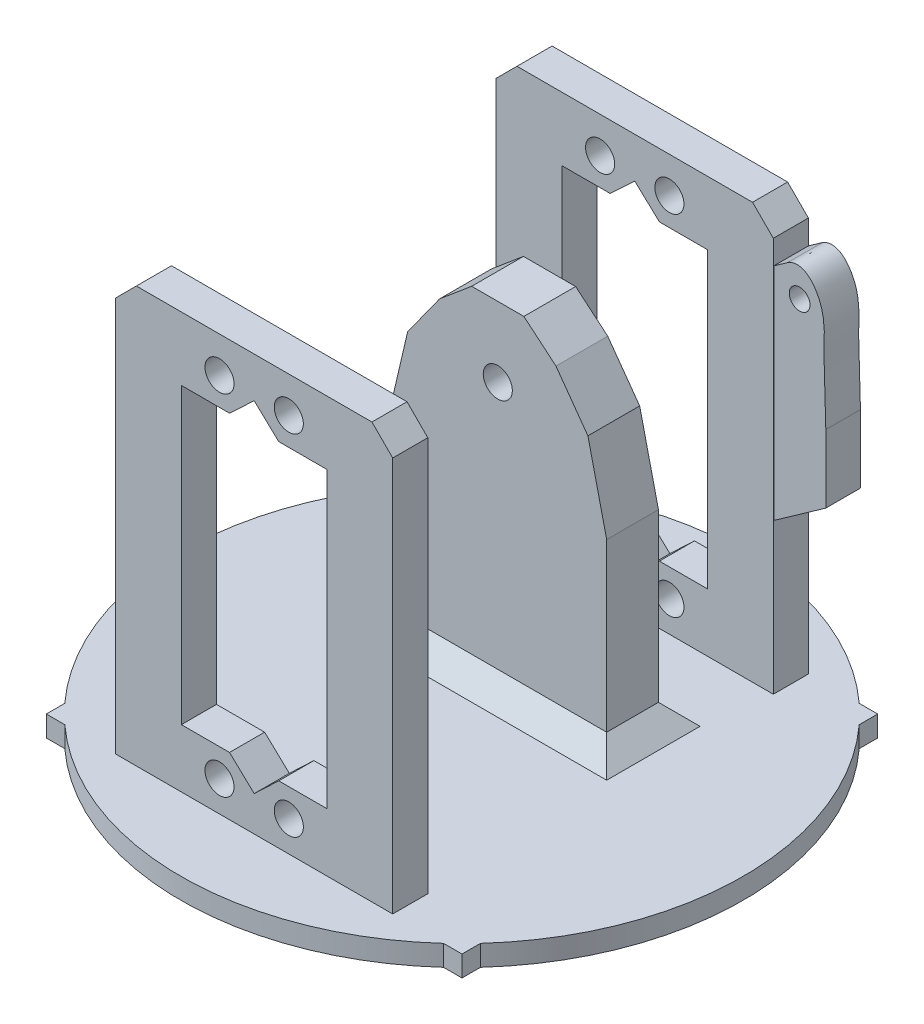
SolidWorks part; units mm, degrees
ref_plane "Plan de face" through (0, 0, 0) normal (0, 0, 1) x (1, 0, 0)
ref_plane "Plan de dessus" through (0, 0, 0) normal (0, 1, 0) x (1, 0, 0)
ref_plane "Plan de droite" through (0, 0, 0) normal (1, 0, 0) x (0, 0, -1)
sketch "Esquisse1" plane through (0, 0, 0) normal (0, 1, 0) x (1, 0, 0)
  line L1 (30, -30) -> (-30, -30)
  line L2 (30, -30) -> (30, 30)
  line L3 (30, 30) -> (-30, 30)
  line L4 (-30, -30) -> (-30, 30)
  line L5 (30, -30) -> (-30, 30) construction
  line L6 (30, 30) -> (-30, -30) construction
  point P0 (0, 0)
  dimension "D1" = 60
  dimension "D2" = 60
extrude "Boss.-Extru.1" add sketch "Esquisse1" along normal blind 3
sketch "Esquisse2" plane through (0, 3, 0) normal (0, 1, 0) x (1, 0, 0)
  line L0 (20, -30) -> (-20, -30)
  line L1 (-30, -30) -> (30, -30) construction
  line L2 (0, -1.65) -> (0, 1.65) construction
  line L3 (-1.65, 0) -> (1.65, 0) construction
  line L4 (20, 30) -> (-20, 30)
  line L5 (-20, -30) -> (-20, -24.9359)
  line L6 (-20, -24.9359) -> (20, -24.9359)
  line L7 (20, -24.9359) -> (20, -30)
  line L8 (-20, 30) -> (-20, 24.9359)
  line L9 (-20, 24.9359) -> (20, 24.9359)
  line L10 (20, 24.9359) -> (20, 30)
  point P7 (0, -30)
  point P11 (-20, -27.468)
  point P16 (-20, 27.468)
  dimension "D1" = 20
extrude "Boss.-Extru.2" add sketch "Esquisse2" along normal blind 60
sketch "Esquisse3" plane through (0, 0, 30) normal (0, 0, 1) x (1, 0, 0)
  line L0 (0, -37.675) -> (0, 37.675) construction
  line L5 (10.5, 53.8193) -> (-10.5, 53.8193)
  line L6 (10.5, 11.4193) -> (-10.5, 11.4193)
  line L7 (-10.5, 53.8193) -> (-10.5, 11.4193)
  line L8 (10.5, 53.8193) -> (10.5, 11.4193)
  circle A0 centre (-5, 57.8193) radius 2.1
  circle A1 centre (5, 57.8193) radius 2.1
  circle A2 centre (-5, 7.4193) radius 2.1
  circle A3 centre (5, 7.4193) radius 2.1
  point P13 (0, 53.8193)
  point P16 (0, 11.4193)
  dimension "D1" = 10
  dimension "D2" = 10
  dimension "D7" = 4.2
  dimension "D3" = 50.4
  dimension "D4" = 4
  dimension "D5" = 4
  dimension "D6" = 10.5
extrude "Enlèv. mat.-Extru.1" cut sketch "Esquisse3" against normal blind 61
sketch "Esquisse4" plane through (0, 3, 0) normal (0, 1, 0) x (1, 0, 0)
  line L0 (0, -37.675) -> (0, 37.675) construction
  line L1 (-15.7182, 5.1641) -> (15.7182, 5.1641)
  line L2 (-15.7182, 5.1641) -> (-15.7182, 12.6359)
  line L3 (-15.7182, 12.6359) -> (15.7182, 12.6359)
  line L4 (15.7182, 5.1641) -> (15.7182, 12.6359)
  line L5 (-15.7182, 5.1641) -> (15.7182, 12.6359) construction
  line L6 (-15.7182, 12.6359) -> (15.7182, 5.1641) construction
  line L7 (-20, 24.9359) -> (20, 24.9359) construction
  line L8 (20, -24.9359) -> (-20, -24.9359) construction
  point P0 (0, 8.9)
  dimension "D1" = 12.3
  dimension "D2" = 30.1
  dimension "D3" = 15.7182
extrude "Boss.-Extru.3" add sketch "Esquisse4" along normal blind 49
sketch "Esquisse5" plane through (0, 0, -5.1641) normal (0, 0, 1) x (1, 0, 0)
  line L0 (0, -37.675) -> (0, 37.675) construction
  line L1 (-15.7182, 3) -> (15.7182, 3) construction
  circle A0 centre (0, 41.8849) radius 2.1
  dimension "D1" = 4.2
  dimension "D2" = 38.8849
extrude "Enlèv. mat.-Extru.2" cut sketch "Esquisse5" against normal blind 49 and the other way blind 49
sketch "Esquisse6" plane through (0, 0, -5.1641) normal (0, 0, 1) x (1, 0, 0)
  line L0 (3.7658, 52) -> (-3.7658, 52)
  line L1 (-15.7182, 52) -> (15.7182, 52) construction
  line L2 (-3.7658, 52) -> (-8.3964, 48.1136)
  line L3 (-8.3964, 48.1136) -> (-13.0095, 41.6972)
  line L4 (-13.0095, 41.6972) -> (-16.0709, 28.5708)
  line L6 (-16.0709, 28.5708) -> (-19.384, 28.5708)
  line L8 (-19.384, 28.5708) -> (-19.384, 55.5697)
  line L9 (-19.384, 55.5697) -> (19.384, 55.5697)
  line L10 (0, -37.675) -> (0, 37.675) construction
  line L11 (19.384, 28.5708) -> (19.384, 55.5697)
  line L12 (16.0709, 28.5708) -> (19.384, 28.5708)
  line L13 (13.0095, 41.6972) -> (16.0709, 28.5708)
  line L14 (8.3964, 48.1136) -> (13.0095, 41.6972)
  line L15 (3.7658, 52) -> (8.3964, 48.1136)
  point P12 (0, 55.5697)
  point P19 (0, 52)
extrude "Enlèv. mat.-Extru.3" cut sketch "Esquisse6" against normal blind 12 and the other way blind 5
sketch "Esquisse11" plane through (0, 0, 30) normal (0, 0, 1) x (1, 0, 0)
  line L0 (-3.5547, 53.8193) -> (0, 57.1568)
  line L1 (10.5, 53.8193) -> (-10.5, 53.8193) construction
  line L2 (0, -37.675) -> (0, 37.675) construction
  line L3 (-3.5547, 53.8193) -> (3.5547, 53.8193)
  line L4 (3.5547, 53.8193) -> (0, 57.1568)
  line L5 (3.5547, 11.4193) -> (0.0082, 8.057)
  line L6 (3.5547, 11.4193) -> (-3.5547, 11.4193)
  line L7 (-3.5547, 11.4193) -> (0.0082, 8.057)
  line L8 (-10.5, 11.4193) -> (10.5, 11.4193) construction
  point P8 (0, 53.8193)
  point P11 (0, 11.4193)
extrude "Enlèv. mat.-Extru.7" cut sketch "Esquisse11" against normal blind 5.6866
mirror "Symétrie1" about plane through (0, 0, 0) normal (0, 0, 1) of "Enlèv. mat.-Extru.7"
sketch "Esquisse12" plane through (0, 0, -30) normal (0, 0, -1) x (-1, 0, 0)
  line L0 (-16.0416, 53.7226) -> (-27.511, 61.81)
  line L1 (-27.511, 61.81) -> (-27.511, 29.9904)
  line L2 (-27.511, 29.9904) -> (-16.0416, 21.903)
  line L3 (-16.0416, 21.903) -> (-16.0416, 53.7226)
extrude "Boss.-Extru.4" add sketch "Esquisse12" against normal blind 5
sketch "Esquisse13" plane through (0, 0, -30) normal (0, 0, -1) x (-1, 0, 0)
  circle A0 centre (-23.7338, 54.2323) radius 1.5
  dimension "D1" = 3
extrude "Enlèv. mat.-Extru.8" cut sketch "Esquisse13" against normal blind 5
sketch "Esquisse14" plane through (0, 0, -30) normal (0, 0, -1) x (-1, 0, 0)
  line L5 (-20, 56.5138) -> (-27.511, 61.81) construction
  line L6 (-21.7182, 57.7253) -> (-22.3131, 61.5715)
  line L7 (-22.3131, 61.5715) -> (-29.1238, 63.5663)
  line L8 (-29.1238, 63.5663) -> (-31.434, 54.2822)
  line L9 (-31.434, 54.2822) -> (-31.8021, 39.8087)
  line L10 (-31.8021, 39.8087) -> (-27.511, 39.8087)
  line L11 (-27.511, 61.81) -> (-27.511, 29.9904) construction
  spline S0 degree 3 poles (-27.511, 39.8087) (-27.4765, 42.4262) (-27.33, 45.1772) (-27.1888, 50.3172) (-27.8341, 55.2939) (-23.9393, 59.4321) (-21.7182, 57.7253) knots 0 0 0 0 0.330124 0.401516 0.713916 1 1 1 1
extrude "Enlèv. mat.-Extru.9" cut sketch "Esquisse14" against normal blind 10
chamfer "Chanfrein1" distance 3 angle 45 4 edges at (-20, 63, 27.468) (20, 63, 27.468) (-20, 63, -27.468) (20, 63, -27.468)
chamfer "Chanfrein2" distance 3 angle 45 4 edges at (15.7182, 3, -8.9) (0, 3, -5.1641) (-15.7182, 3, -8.9) (0, 3, -12.6359)
sketch "Esquisse15" plane through (0, 0, 0) normal (0, -1, 0) x (1, 0, 0)
  circle A0 centre (0, 0) radius 40.5854
extrude "Boss.-Extru.5" add sketch "Esquisse15" against normal blind 3
sketch "Esquisse16" plane through (0, 0, 0) normal (0, -1, 0) x (1, 0, 0)
  line L0 (1.5, -2) -> (-1.5, -2)
  line L1 (37.675, 0) -> (-37.675, 0) construction
  line L2 (1.5, 2) -> (-1.5, 2)
  circle A0 centre (0, 0) radius 2.5 construction
  circle A1 centre (0, 0) radius 4
  spline S0 degree 3 poles (1.5, 2) (1.9581, 1.6571) (2.5612, 0.7502) (2.4981, -0.8784) (1.9051, -1.696) (1.5, -2) knots 0 0 0 0 0.369168 0.672223 1 1 1 1
  spline S1 degree 3 poles (-1.5, 2) (-1.9587, 1.658) (-2.5333, 0.7881) (-2.5172, -0.8222) (-1.9429, -1.6701) (-1.5, -2) knots 0 0 0 0 0.368917 0.642209 1 1 1 1
  dimension "D1" = 5
  dimension "D3" = 8
  dimension "D2" = 3
extrude "Boss.-Extru.6" add sketch "Esquisse16" along normal blind 5.5
sketch "Esquisse17" plane through (0, 0, 0) normal (0, -1, 0) x (1, 0, 0)
  circle A0 centre (0, 0) radius 31
  circle A1 centre (0, 0) radius 34
  dimension "D1" = 62
  dimension "D2" = 68
extrude "Boss.-Extru.7" add sketch "Esquisse17" along normal blind 1.5
